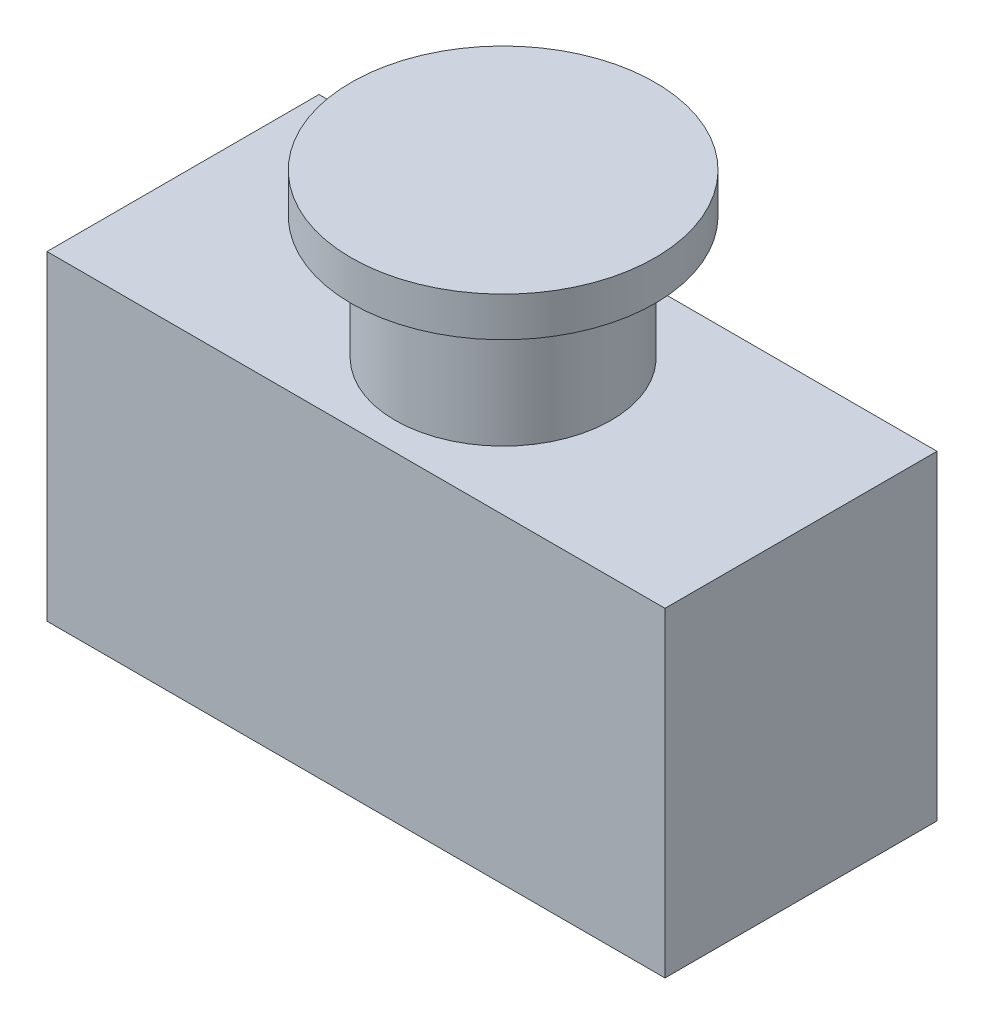
SolidWorks part; units mm, degrees
ref_plane "Front Plane" through (0, 0, 0) normal (0, 0, 1) x (1, 0, 0)
ref_plane "Top Plane" through (0, 0, 0) normal (0, 1, 0) x (1, 0, 0)
ref_plane "Right Plane" through (0, 0, 0) normal (1, 0, 0) x (0, 0, -1)
sketch "Sketch1" plane through (0, 0, 0) normal (0, 1, 0) x (1, 0, 0)
  line L1 (-34.1128, 32.553) -> (275.7672, 32.553)
  line L2 (-34.1128, 32.553) -> (-34.1128, -103.845)
  line L3 (-34.1128, -103.845) -> (275.7672, -103.845)
  line L4 (275.7672, 32.553) -> (275.7672, -103.845)
  dimension "D1" = 309.88
  dimension "D2" = 136.398
extrude "Extrude1" add sketch "Sketch1" along normal blind 160.528
sketch "Sketch2" plane through (0, 160.528, 0) normal (0, 1, 0) x (1, 0, 0)
  line L0 (-34.1128, -35.646) -> (126.4152, -35.646) construction
  line L1 (-34.1128, 32.553) -> (-34.1128, -103.845) construction
  line L2 (-34.1128, 32.553) -> (275.7672, -103.845) construction
  line L3 (-34.1128, -103.845) -> (275.7672, 32.553) construction
  circle A0 centre (126.4152, -35.646) radius 54.2383
  point P15 (120.8272, -35.646)
  dimension "D1" = 160.528
extrude "Extrude2" add sketch "Sketch2" along normal blind 81.534
sketch "Sketch3" plane through (0, 242.062, 0) normal (0, 1, 0) x (1, 0, 0)
  circle A0 centre (126.4152, -35.646) radius 76.2
  dimension "D1" = 152.4
extrude "Extrude3" add sketch "Sketch3" against normal blind 19.812
